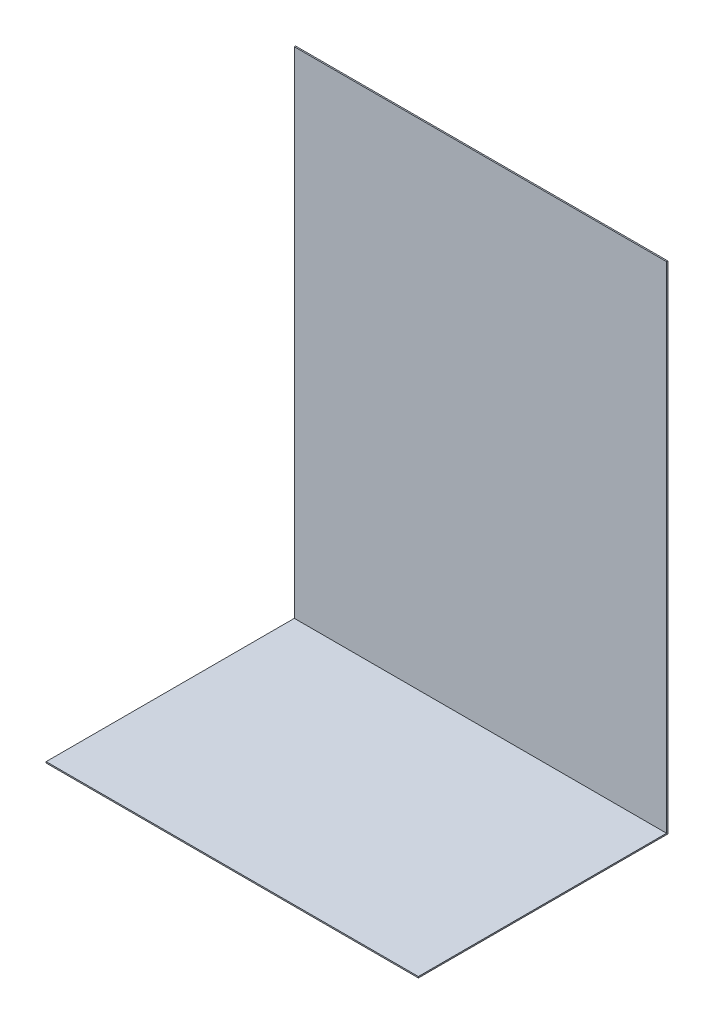
SolidWorks part; units mm, degrees
ref_plane "Front Plane" through (0, 0, 0) normal (0, 0, 1) x (1, 0, 0)
ref_plane "Top Plane" through (0, 0, 0) normal (0, 1, 0) x (1, 0, 0)
ref_plane "Right Plane" through (0, 0, 0) normal (1, 0, 0) x (0, 0, -1)
sketch "Sketch1" plane through (0, 0, 0) normal (0, 0, 1) x (1, 0, 0)
  line L1 (-914.4, 1219.2) -> (914.4, 1219.2)
  line L2 (-914.4, 1219.2) -> (-914.4, -1219.2)
  line L3 (-914.4, -1219.2) -> (914.4, -1219.2)
  line L4 (914.4, 1219.2) -> (914.4, -1219.2)
  line L5 (-914.4, 1219.2) -> (914.4, -1219.2) construction
  line L6 (-914.4, -1219.2) -> (914.4, 1219.2) construction
  point P0 (0, 0)
  dimension "D1" = 1828.8
  dimension "D2" = 2438.4
extrude "Boss-Extrude1" add sketch "Sketch1" along normal blind 6.35
sketch "Sketch2" plane through (0, 0, 6.35) normal (0, 0, 1) x (1, 0, 0)
  line L0 (914.4, -1219.2) -> (914.4, 1219.2) construction
  line L1 (-914.4, -1219.2) -> (914.4, -1219.2)
  line L2 (-914.4, -1219.2) -> (-914.4, -1212.85)
  line L3 (-914.4, -1212.85) -> (914.4, -1212.85)
  line L4 (914.4, -1219.2) -> (914.4, -1212.85)
  dimension "D1" = 6.35
extrude "Boss-Extrude2" add sketch "Sketch2" along normal blind 1219.2
